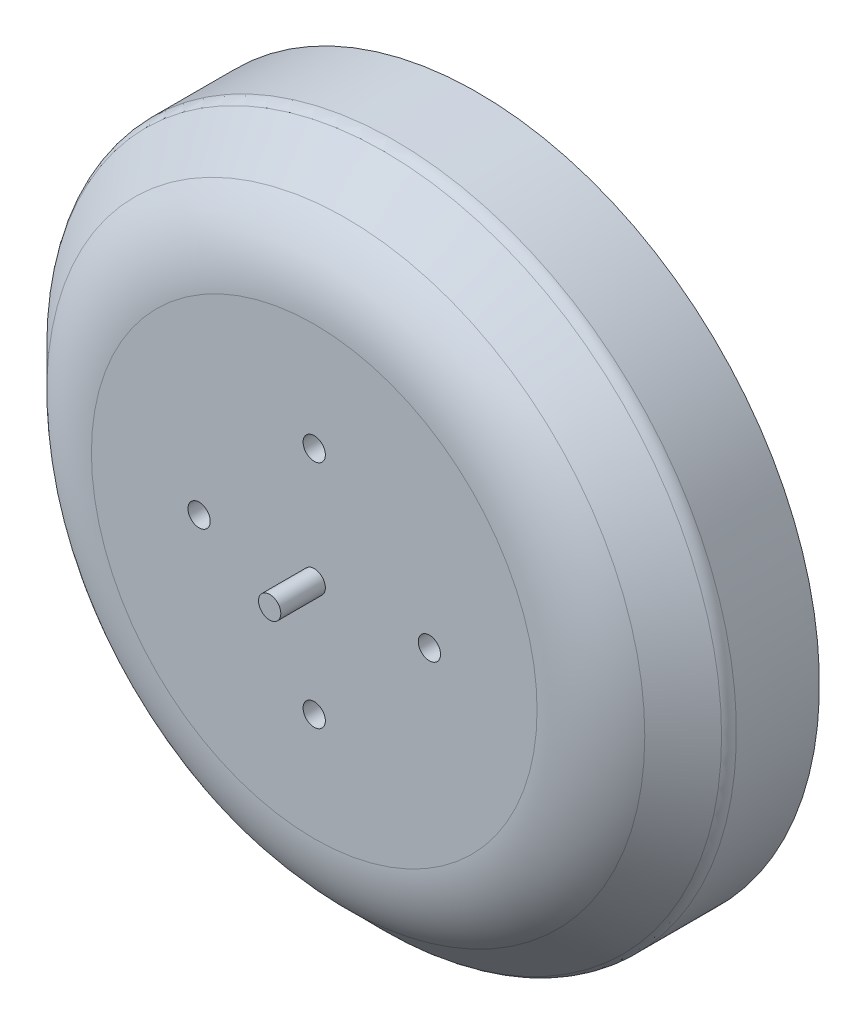
SolidWorks part; units mm, degrees
ref_plane "Front Plane" through (0, 0, 0) normal (0, 0, 1) x (1, 0, 0)
ref_plane "Top Plane" through (0, 0, 0) normal (0, 1, 0) x (1, 0, 0)
ref_plane "Right Plane" through (0, 0, 0) normal (1, 0, 0) x (0, 0, -1)
sketch "Sketch1" plane through (0, 0, 0) normal (0, 1, 0) x (1, 0, 0)
  line L0 (28, 45.5) -> (0, 45.5)
  line L1 (0, 45.5) -> (0, 16.5)
  line L2 (0, 16.5) -> (36, 16.5)
  line L3 (36, 16.5) -> (46, 26.5)
  line L4 (46, 26.5) -> (46, 40.5)
  line L5 (46, 40.5) -> (28, 45.5)
  line L6 (0, 45.5) -> (0, 16.5) construction
revolve "Revolve1" add sketch "Sketch1" angle 360 about L6
sketch "Sketch2" plane through (0, 0, -45.5) normal (0, 0, -1) x (-1, 0, 0)
  line L0 (-9.815, 0) -> (-4.9075, 8.5)
  line L1 (-4.9075, 8.5) -> (4.9075, 8.5)
  line L2 (4.9075, 8.5) -> (9.815, 0)
  line L3 (9.815, 0) -> (4.9075, -8.5)
  line L4 (4.9075, -8.5) -> (-4.9075, -8.5)
  line L5 (-4.9075, -8.5) -> (-9.815, 0)
extrude "Boss-Extrude1" add sketch "Sketch2" along normal blind 4
sketch "Sketch3" plane through (0, 0, -16.5) normal (0, 0, 1) x (1, 0, 0)
  circle A0 centre (0, 0) radius 1.5
extrude "Boss-Extrude2" add sketch "Sketch3" along normal blind 6
hole_wizard "Ø3.0 (3) Diameter Hole1" positions "Sketch5" profile "Sketch4" hole size "Ø3.0" standard "ANSI Metric"
sketch "Sketch5" plane through (0, 0, -16.5) normal (0, 0, 1) x (1, 0, 0)
  point P0 (-15.5, 0)
  point P1 (0, 15.5)
  point P2 (0, -15.5)
  point P3 (15.5, 0)
sketch "Sketch4" plane through (-15.5, 0, -16.5) normal (1, 0, 0) x (0, -1, 0)
  line L0 (0, 0) -> (0, 10)
  line L1 (0, 10) -> (1.5, 10)
  line L2 (1.5, 10) -> (1.5, 0)
  line L5 (1.5, 0) -> (0, 0)
  line L10 (0, 10) -> (-1.5, 10) construction
  line L11 (0, -6.35) -> (0, 107.95) construction
  dimension "Hole Dia." = 3
  dimension "Hole Depth" = 10
  dimension "Drill Angle" = 180
fillet "Fillet2" radius 14.5 1 edges at (36, 0, -16.5)
fillet "Fillet3" radius 2 1 edges at (46, 0, -26.5)
sketch "Sketch8" plane through (0, 0, -45.5) normal (0, 0, -1) x (-1, 0, 0)
  circle A0 centre (0, 0) radius 46
  circle A1 centre (0, 0) radius 46 construction
  circle A2 centre (0, 0) radius 9.815
extrude "Cut-Extrude1" cut sketch "Sketch8" against normal blind 7 and the other way through all
